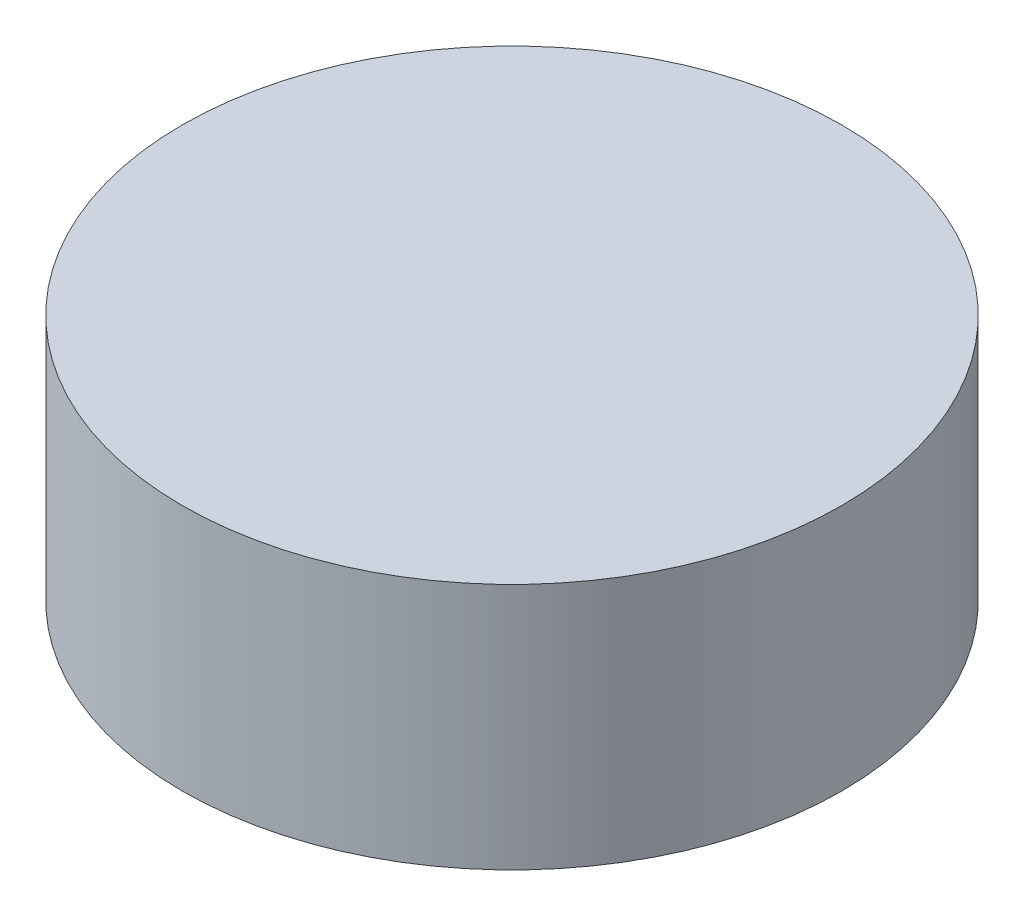
SolidWorks part; units mm, degrees
ref_plane "Front Plane" through (0, 0, 0) normal (0, 0, 1) x (1, 0, 0)
ref_plane "Top Plane" through (0, 0, 0) normal (0, 1, 0) x (1, 0, 0)
ref_plane "Right Plane" through (0, 0, 0) normal (1, 0, 0) x (0, 0, -1)
sketch "Sketch1" plane through (0, 0, 0) normal (0, 1, 0) x (1, 0, 0)
  line L0 (-0.751, 3.4185) -> (-0.7543, 14.4804)
  line L5 (3.336, -1.0588) -> (12.9175, -6.5869)
  line L6 (-0.6988, 14.4831) -> (0, 3.2868) construction
  line L7 (0, 3.2868) -> (0.6988, 14.4831) construction
  line L8 (2.5864, -2.3581) -> (12.1679, -7.8862)
  line L9 (0.749, 3.4189) -> (0.7457, 14.4808)
  line L10 (-2.585, -2.3596) -> (-12.1632, -7.8934)
  line L11 (-3.3354, -1.0608) -> (-12.9136, -6.5946)
  arc A0 (2.5864, -2.3581) -> (3.336, -1.0588) centre (0, 0) ccw
  circle A1 centre (0, 0) radius 16
  arc A2 (-12.1632, -7.8934) -> (12.1679, -7.8862) centre (0, 0) ccw
  arc A3 (-0.6988, 14.4831) -> (-12.9136, -6.5946) centre (0, 0) ccw
  arc A4 (12.9175, -6.5869) -> (0.6988, 14.4831) centre (0, 0) ccw
  arc A5 (-3.3354, -1.0608) -> (-2.585, -2.3596) centre (0, 0) ccw
  arc A6 (0.749, 3.4189) -> (-0.751, 3.4185) centre (0, 0) ccw
  point P5 (0, 3.2868)
  point P23 (0, 0)
  dimension "D1" = 7
  dimension "D2" = 32
  dimension "D3" = 1.5
  dimension "D4" = 1.5
  dimension "D5" = 3
extrude "Boss-Extrude1" add sketch "Sketch1" along normal blind 10.5
sketch "Sketch2" plane through (0, 10.5, 0) normal (0, 1, 0) x (1, 0, 0)
  circle A0 centre (0, 0) radius 16
extrude "Boss-Extrude2" add sketch "Sketch2" along normal blind 1.5
sketch "Sketch3" plane through (0, 10.5, 0) normal (0, -1, 0) x (1, 0, 0)
  line L0 (-2.5981, -1.5) -> (2.5981, -1.5)
  circle A0 centre (0, 0) radius 3.5
  arc A1 (2.5981, -1.5) -> (-2.5981, -1.5) centre (0, 0) ccw
  dimension "D1" = 6
  dimension "D2" = 1.5
extrude "Boss-Extrude3" add sketch "Sketch3" along normal blind 10.5
